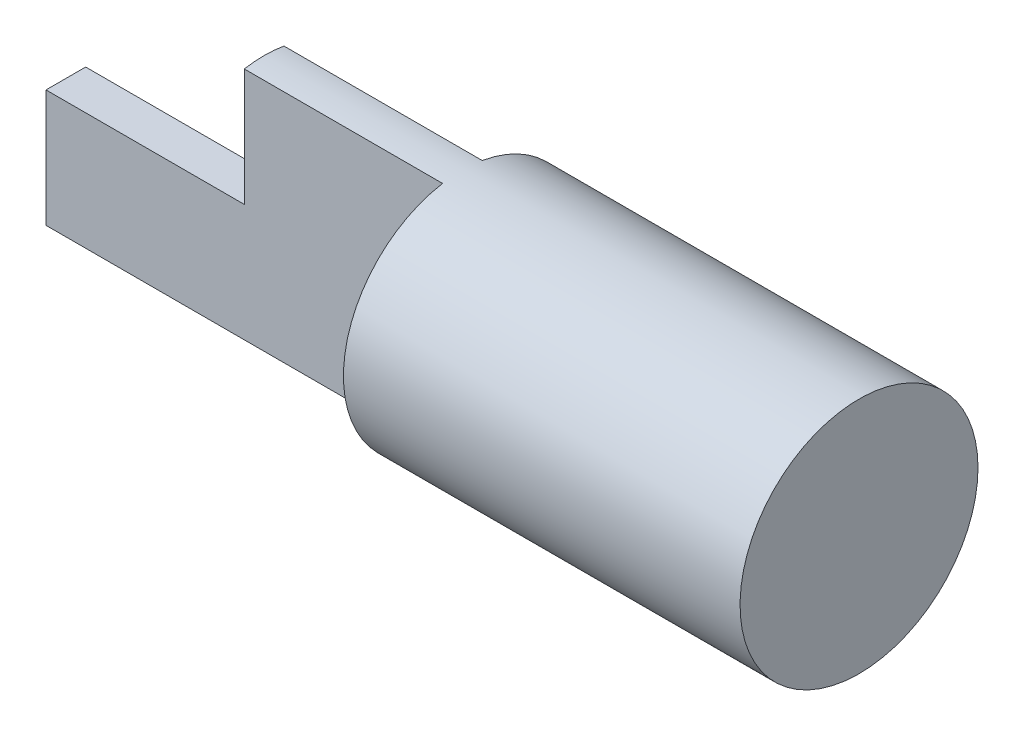
SolidWorks part; units mm, degrees
ref_plane "Front Plane" through (0, 0, 0) normal (0, 0, 1) x (1, 0, 0)
ref_plane "Top Plane" through (0, 0, 0) normal (0, 1, 0) x (1, 0, 0)
ref_plane "Right Plane" through (0, 0, 0) normal (1, 0, 0) x (0, 0, -1)
sketch "Sketch1" plane through (0, 0, 0) normal (1, 0, 0) x (0, 0, -1)
  circle A0 centre (0, 0) radius 30
extrude "Boss-Extrude1" add sketch "Sketch1" along normal blind 100
sketch "Sketch2" plane through (0, 0, 0) normal (-1, 0, 0) x (0, 0, 1)
  line L0 (0, -30) -> (0, 30) construction
  line L1 (5, -29.5804) -> (5, 29.5804)
  line L2 (-5, 29.5804) -> (-5, -29.5804)
  arc A0 (-5, 29.5804) -> (5, 29.5804) centre (0, 0) cw
  circle A1 centre (0, 0) radius 30 construction
  arc A2 (-5, -29.5804) -> (5, -29.5804) centre (0, 0) ccw
  dimension "D1" = 5
  dimension "D2" = 5
extrude "Boss-Extrude2" add sketch "Sketch2" along normal blind 50
sketch "Sketch3" plane through (-50, 0, 0) normal (-1, 0, 0) x (0, 0, 1)
  line L0 (-5, 0) -> (5, 0)
  line L1 (-5, 29.5804) -> (-5, -29.5804) construction
  line L2 (5, -29.5804) -> (5, 29.5804) construction
  line L3 (5, 0) -> (5, 29.5804)
  line L4 (-5, 0) -> (-5, 29.5804)
  line L5 (5, -29.5804) -> (5, 29.5804)
  line L6 (-5, 29.5804) -> (-5, -29.5804)
  line L7 (5, -29.5804) -> (5, 0)
  line L8 (-5, 0) -> (-5, -29.5804)
  arc A2 (-5, -29.5804) -> (5, -29.5804) centre (0, 0) ccw
  arc A3 (5, 29.5804) -> (-5, 29.5804) centre (0, 0) ccw
  arc A4 (-5, -29.5804) -> (5, -29.5804) centre (0, 0) ccw
  arc M5 (-5, -29.5804) -> (5, -29.5804) centre (0, 0) ccw
  line M6 (5, -29.5804) -> (5, 29.5804)
  line M8 (-5, 29.5804) -> (-5, -29.5804)
  dimension "D1" = 0
extrude "Boss-Extrude3" add sketch "Sketch3" along normal blind 50 contours L0 M8 M5 M6
